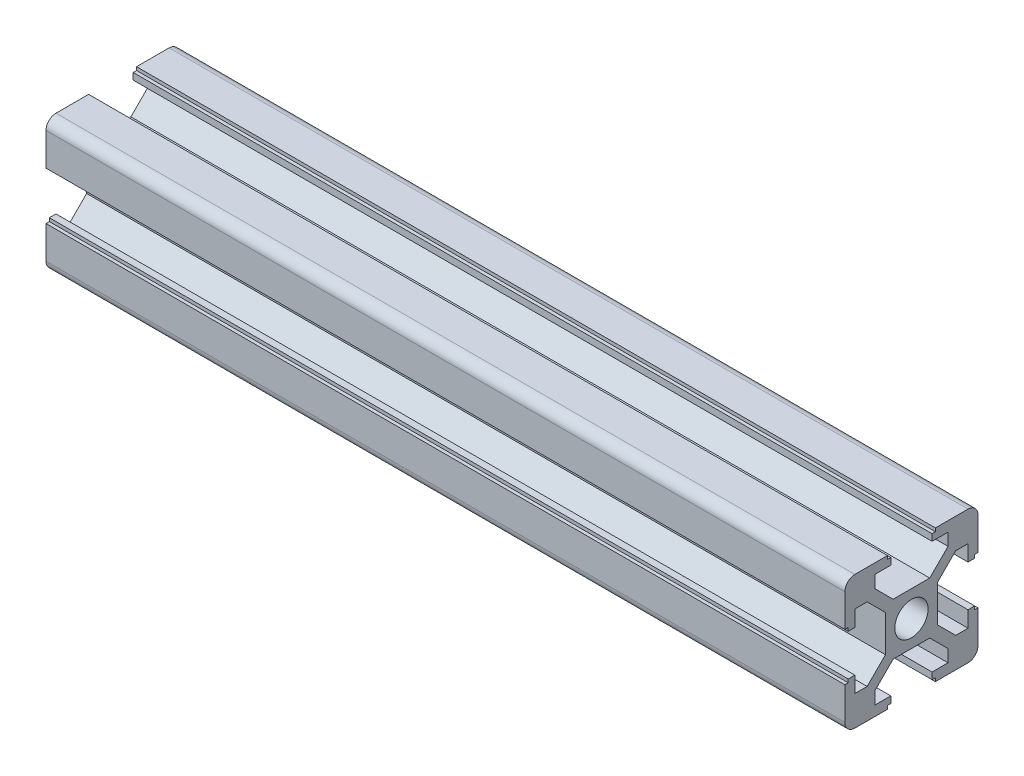
SolidWorks part; units mm, degrees
ref_plane "前视基准面" through (0, 0, 0) normal (0, 0, 1) x (1, 0, 0)
ref_plane "上视基准面" through (0, 0, 0) normal (0, 1, 0) x (1, 0, 0)
ref_plane "右视基准面" through (0, 0, 0) normal (1, 0, 0) x (0, 0, -1)
sketch "草图1" plane through (0, 0, 0) normal (0, 1, 0) x (1, 0, 0)
  line L0 (0, 0) -> (120, 0)
  dimension "D1" = 120
other "铝型材 20 X 20 X R1.5(1)"
ref_plane "基准面1" through (0, 0, 0) normal (1, 0, 0) x (0, 0, -1)
sketch "Sketch1" plane through (0, 0, 0) normal (1, 0, 0) x (0, 0, -1)
  line L0 (-3.6, 10) -> (-3.6, 9.5)
  line L1 (-3.6, 9.5) -> (-3.1, 9.5)
  line L2 (-3.1, 9.5) -> (-3.1, 8.5)
  line L3 (-3.1, 8.5) -> (-5.5, 8.5)
  line L4 (-8.5, -10) -> (-3.6, -10)
  line L5 (-10, -8.5) -> (-10, -3.6)
  line L6 (8.5, 10) -> (3.6, 10)
  line L7 (10, 8.5) -> (10, 3.6)
  line L8 (0, 14.8756) -> (0, 0) construction
  line L9 (0, 0) -> (14.1675, 0) construction
  line L10 (-5.5, 8.5) -> (-5.5, 6.65)
  line L11 (-5.5, 6.65) -> (-2.75, 3.9)
  line L12 (-2.75, 3.9) -> (2.75, 3.9)
  line L13 (5.5, 6.65) -> (2.75, 3.9)
  line L14 (5.5, 8.5) -> (5.5, 6.65)
  line L15 (3.1, 8.5) -> (5.5, 8.5)
  line L16 (3.1, 9.5) -> (3.1, 8.5)
  line L17 (3.6, 9.5) -> (3.1, 9.5)
  line L18 (3.6, 10) -> (3.6, 9.5)
  line L19 (-3.6, 10) -> (-8.5, 10)
  line L20 (10, 3.6) -> (9.5, 3.6)
  line L21 (9.5, 3.6) -> (9.5, 3.1)
  line L22 (9.5, 3.1) -> (8.5, 3.1)
  line L23 (8.5, 3.1) -> (8.5, 5.5)
  line L24 (8.5, 5.5) -> (6.65, 5.5)
  line L25 (6.65, 5.5) -> (3.9, 2.75)
  line L26 (3.9, 2.75) -> (3.9, -2.75)
  line L27 (6.65, -5.5) -> (3.9, -2.75)
  line L28 (8.5, -5.5) -> (6.65, -5.5)
  line L29 (8.5, -3.1) -> (8.5, -5.5)
  line L30 (9.5, -3.1) -> (8.5, -3.1)
  line L31 (9.5, -3.6) -> (9.5, -3.1)
  line L32 (10, -3.6) -> (9.5, -3.6)
  line L33 (3.6, -10) -> (3.6, -9.5)
  line L34 (3.6, -9.5) -> (3.1, -9.5)
  line L35 (3.1, -9.5) -> (3.1, -8.5)
  line L36 (3.1, -8.5) -> (5.5, -8.5)
  line L37 (5.5, -8.5) -> (5.5, -6.65)
  line L38 (5.5, -6.65) -> (2.75, -3.9)
  line L39 (2.75, -3.9) -> (-2.75, -3.9)
  line L40 (-5.5, -6.65) -> (-2.75, -3.9)
  line L41 (-5.5, -8.5) -> (-5.5, -6.65)
  line L42 (-3.1, -8.5) -> (-5.5, -8.5)
  line L43 (-3.1, -9.5) -> (-3.1, -8.5)
  line L44 (-3.6, -9.5) -> (-3.1, -9.5)
  line L45 (-3.6, -10) -> (-3.6, -9.5)
  line L46 (-10, -3.6) -> (-9.5, -3.6)
  line L47 (-9.5, -3.6) -> (-9.5, -3.1)
  line L48 (-9.5, -3.1) -> (-8.5, -3.1)
  line L49 (-8.5, -3.1) -> (-8.5, -5.5)
  line L50 (-8.5, -5.5) -> (-6.65, -5.5)
  line L51 (-6.65, -5.5) -> (-3.9, -2.75)
  line L52 (-3.9, -2.75) -> (-3.9, 2.75)
  line L53 (-6.65, 5.5) -> (-3.9, 2.75)
  line L54 (-8.5, 5.5) -> (-6.65, 5.5)
  line L55 (-8.5, 3.1) -> (-8.5, 5.5)
  line L56 (-9.5, 3.1) -> (-8.5, 3.1)
  line L57 (-9.5, 3.6) -> (-9.5, 3.1)
  line L58 (-10, 3.6) -> (-9.5, 3.6)
  line L59 (3.6, -10) -> (8.5, -10)
  line L60 (-10, 3.6) -> (-10, 8.5)
  line L61 (10, -3.6) -> (10, -8.5)
  circle A0 centre (0, 0) radius 2.5
  arc A1 (-10, 8.5) -> (-8.5, 10) centre (-8.5, 8.5) cw
  arc A2 (10, 8.5) -> (8.5, 10) centre (8.5, 8.5) ccw
  arc A3 (-8.5, -10) -> (-10, -8.5) centre (-8.5, -8.5) cw
  arc A4 (8.5, -10) -> (10, -8.5) centre (8.5, -8.5) ccw
  point P0 (-10, 0)
  point P1 (10, 0)
  point P2 (0, 10)
  point P3 (0, -10)
  point P4 (0, 0)
  point P5 (-10, -10)
  point P6 (10, -10)
  point P7 (10, 10)
  point P8 (-10, 10)
  point P13 (0, 0)
  point P36 (-10, 10)
  point P39 (10, 10)
  dimension "D1" = 11
  dimension "D2" = 20
  dimension "D3" = 6.2
  dimension "D4" = 7.2
  dimension "D5" = 6.1
  dimension "D6" = 5
  dimension "D7" = 1.5
  dimension "D8" = 45
  dimension "D9" = 0.5
  dimension "D10" = 1
  dimension "D11" = 5.5
